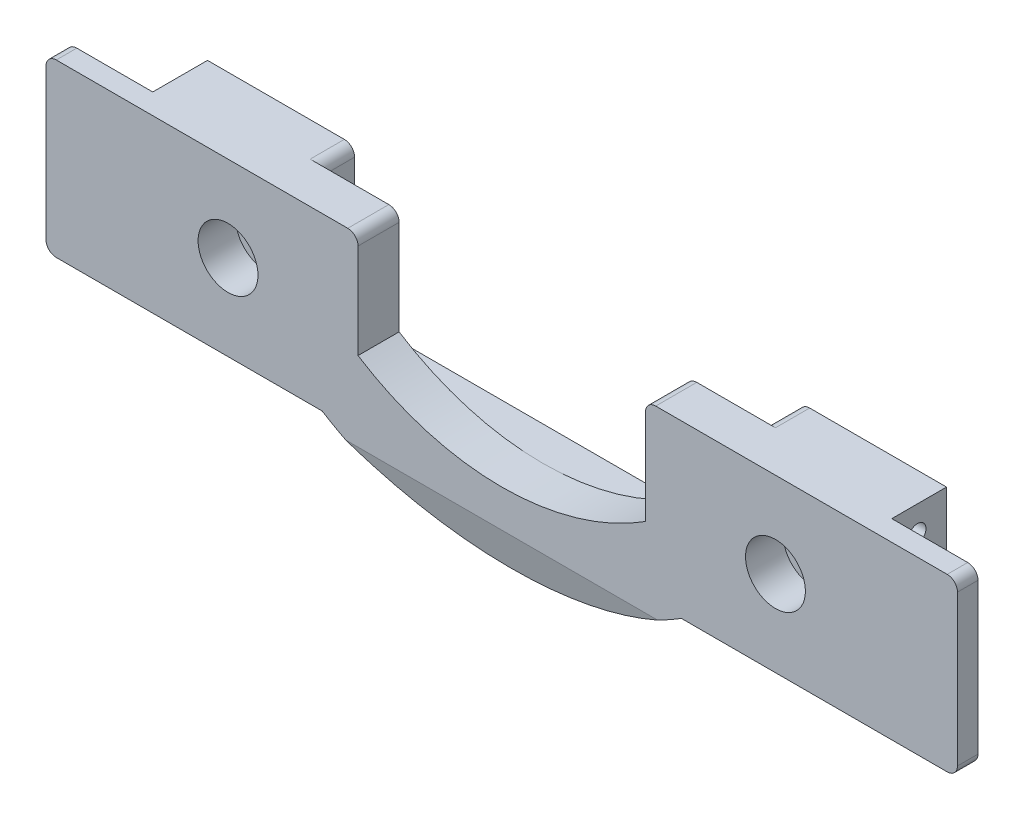
SolidWorks part; units mm, degrees
ref_plane "前视基准面" through (0, 0, 0) normal (0, 0, 1) x (1, 0, 0)
ref_plane "上视基准面" through (0, 0, 0) normal (0, 1, 0) x (1, 0, 0)
ref_plane "右视基准面" through (0, 0, 0) normal (1, 0, 0) x (0, 0, -1)
sketch "草图1" plane through (0, 0, 0) normal (0, 0, 1) x (1, 0, 0)
  line L0 (44.1636, 0) -> (0, 0) construction
  line L1 (-133.2, 25) -> (133.2, 25)
  line L2 (-133.2, 25) -> (-133.2, -25)
  line L3 (-133.2, -25) -> (133.2, -25)
  line L4 (133.2, 25) -> (133.2, -25)
  line L5 (0, 0) -> (0, 61.7472) construction
  dimension "D1" = 266.4
  dimension "D2" = 50
extrude "凸台-拉伸1" add sketch "草图1" against normal blind 22
sketch "草图2" plane through (0, 25, 0) normal (0, 1, 0) x (1, 0, 0)
  line L0 (0, 0) -> (0, 41.2161) construction
  line L1 (-133.2, 22) -> (-108, 22)
  line L2 (-133.2, 22) -> (-133.2, 6)
  line L3 (-133.2, 6) -> (-108, 6)
  line L4 (-108, 22) -> (-108, 6)
  line L5 (108, 22) -> (108, 6)
  line L6 (133.2, 6) -> (108, 6)
  line L7 (133.2, 22) -> (133.2, 6)
  line L8 (133.2, 22) -> (108, 22)
  line L9 (133.2, 0) -> (-133.2, 0) construction
  dimension "D1" = 216
  dimension "D2" = 6
extrude "切除-拉伸1" cut sketch "草图2" against normal through all
sketch "草图5" plane through (0, 0, -22) normal (0, 0, -1) x (-1, 0, 0)
  line L0 (-108, 25) -> (108, 25) construction
  line L1 (-65, 25) -> (65, 25)
  line L2 (-65, 25) -> (-65, -18)
  line L3 (-65, -18) -> (65, -18)
  line L4 (65, 25) -> (65, -18)
  line L5 (0, 0) -> (0, 42.4355) construction
  dimension "D1" = 130
  dimension "D2" = 43
extrude "切除-拉伸4" cut sketch "草图5" against normal blind 10
sketch "草图3" plane through (0, 0, 0) normal (0, 0, 1) x (1, 0, 0)
  line L0 (-42, 25) -> (-42, -5.7267)
  line L1 (133.2, 25) -> (-133.2, 25) construction
  line L2 (0, 0) -> (0, 60) construction
  line L3 (42, 25) -> (42, -5.7267)
  line L4 (-42, 25) -> (42, 25)
  line L5 (65, -18) -> (-65, -18) construction
  arc A0 (-42, -5.7267) -> (42, -5.7267) centre (0, 60) ccw
  dimension "D3" = 156
  dimension "D1" = 84
extrude "切除-拉伸2" cut sketch "草图3" against normal through all
sketch "草图6" plane through (0, 0, 0) normal (0, 0, 1) x (1, 0, 0)
  line L0 (-52.5, -25) -> (52.5, -25)
  line L1 (-133.2, -25) -> (133.2, -25) construction
  arc A0 (-52.5, -25) -> (52.5, -25) centre (0, 60.1102) ccw
  dimension "D1" = 200
  dimension "D2" = 105
extrude "凸台-拉伸2" add sketch "草图6" against normal up to surface (22 mm away) up to face at (0, 1.75, -22)
sketch "草图7" plane through (0, 0, 0) normal (1, 0, 0) x (0, 0, -1)
  line L0 (22, -39.8898) -> (22, -26.8898)
  line L1 (22, -26.8898) -> (9, -39.8898)
  line L2 (0, -39.8898) -> (22, -39.8898) construction
  line L3 (9, -39.8898) -> (22, -39.8898)
  line L4 (0, -39.8898) -> (2.7, -39.8898)
  line L5 (2.7, -39.8898) -> (0, -28.8898)
  line L6 (0, -25) -> (0, -39.8898) construction
  line L7 (0, -28.8898) -> (0, -39.8898)
  dimension "D1" = 13
  dimension "D2" = 13
  dimension "D3" = 2.7
  dimension "D4" = 11
extrude "切除-拉伸5" cut sketch "草图7" against normal mid plane 500
hole_wizard "孔1" positions "草图9" profile "草图8" legacy
sketch "草图9" plane through (0, 0, 0) normal (0, 0, 1) x (1, 0, 0)
  line L0 (0, 0) -> (0, 53.7703) construction
  line L2 (0, 0) -> (80, 0) construction
  point P1 (80, 0)
  point P8 (-80, 0)
  dimension "D1" = 160
sketch "草图8" plane through (80, 0, 0) normal (1, 0, 0) x (0, -1, 0)
  line L0 (0, 0) -> (0, 100)
  line L1 (0, 100) -> (5.5, 100)
  line L2 (5.5, 100) -> (5.5, 11)
  line L3 (5.5, 11) -> (8.75, 11)
  line L4 (8.75, 11) -> (8.75, 0)
  line L5 (8.75, 0) -> (0, 0)
  line L6 (0, 110) -> (0, -10) construction
  dimension "直径" = 11
  dimension "深度" = 100
  dimension "柱坑直径" = 17.5
  dimension "柱坑深度" = 11
sketch "草图10" plane through (0, 0, -22) normal (0, 0, -1) x (-1, 0, 0)
  circle A0 centre (80, 0) radius 10
  circle A1 centre (-80, 0) radius 10
  dimension "D1" = 20
extrude "切除-拉伸6" cut sketch "草图10" against normal blind 2
hole_wizard "M6x1.0 螺纹孔1" positions "草图12" profile "草图11" tap size "M6x1.0" standard "JIS"
sketch "草图12" plane through (-108, 0, 0) normal (-1, 0, 0) x (0, 0, 1)
  line L0 (0, 0) -> (-35.1274, 0) construction
  line L2 (-22, -25) -> (-22, 25) construction
  point P1 (-13.5, -17.5)
  point P3 (-13.5, 17.5)
  dimension "D1" = 35
  dimension "D2" = 8.5
sketch "草图11" plane through (-108, -17.5, -13.5) normal (0, 1, 0) x (0, 0, 1)
  line L0 (0, 0) -> (0, 16.5022)
  line L1 (0, 16.5022) -> (2.5, 15)
  line L2 (2.5, 15) -> (2.5, 0)
  line L5 (2.5, 0) -> (0, 0)
  line L10 (0, 16.5022) -> (-2.5, 15) construction
  line L11 (0, -6.35) -> (0, 107.95) construction
  dimension "螺纹孔钻头直径" = 5
  dimension "螺纹孔钻头深度" = 15
  dimension "导头角度" = 118
cosmetic thread "孔螺蚊线1" parameters "D1"=12, "D2"=6
cosmetic thread "孔螺蚊线2" parameters "D1"=12, "D2"=6
mirror "镜向1" about plane through (0, 0, 0) normal (1, 0, 0) of "M6x1.0 螺纹孔1"
fillet "圆角1" radius 3 10 edges at (-133.2, -25, -3) (-133.2, 25, -3) (133.2, -25, -3) (133.2, 25, -3) (42, 25, -6) (-42, 25, -6) (-65, 25, -17) (-65, -18, -17) (65, 25, -17) (65, -18, -17)
